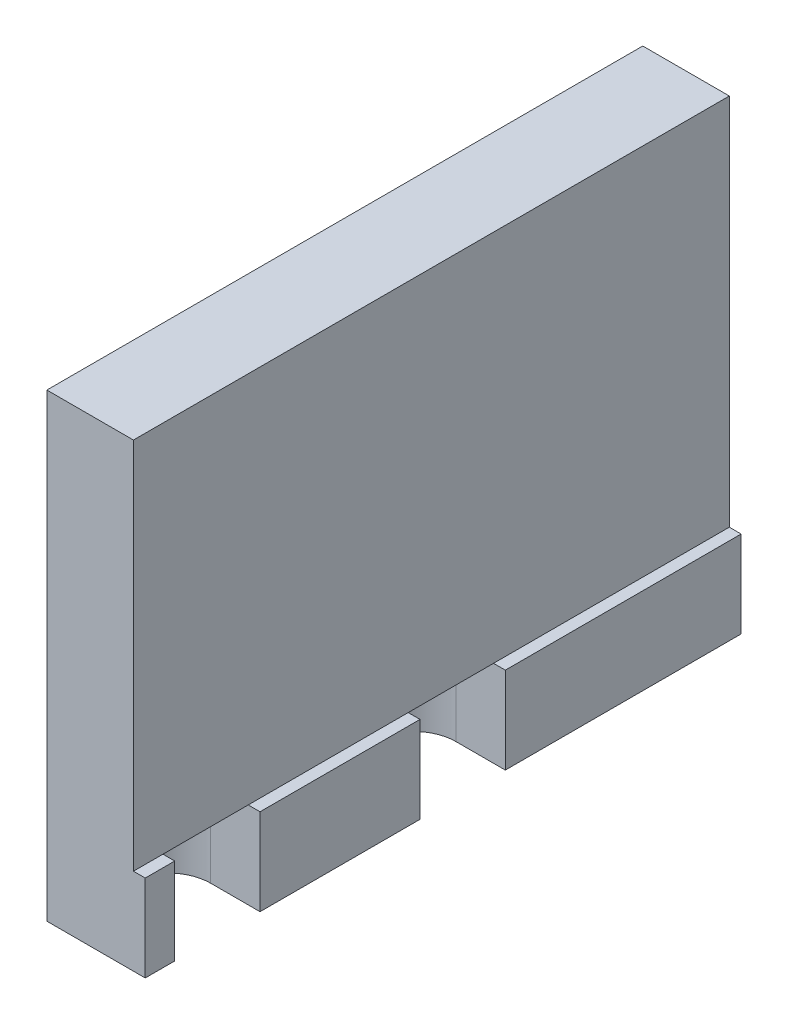
SolidWorks part; units mm, degrees
ref_plane "Front Plane" through (0, 0, 0) normal (0, 0, 1) x (1, 0, 0)
ref_plane "Top Plane" through (0, 0, 0) normal (0, 1, 0) x (1, 0, 0)
ref_plane "Right Plane" through (0, 0, 0) normal (1, 0, 0) x (0, 0, -1)
sketch "Sketch1" plane through (0, 0, 0) normal (0, 0, 1) x (1, 0, 0)
  line L0 (0, 0) -> (-6.8183, 0)
  line L1 (-6.8183, 0) -> (-6.8183, 76.4)
  line L2 (-6.8183, 76.4) -> (-0.8183, 76.4)
  line L3 (-0.8183, 76.4) -> (-0.8183, 6)
  line L4 (-0.8183, 6) -> (0, 6)
  line L5 (0, 6) -> (0, 0)
  line L6 (-0.8183, 44.108) -> (-0.8183, 16.1905) construction
  dimension "D1" = 6
  dimension "D2" = 6
extrude "Boss-Extrude1" add sketch "Sketch1" along normal blind 27 contours L5 L0 L1 L2 L3 L4
sketch "Sketch2" plane through (0, 0, 0) normal (0, 0, -1) x (-1, 0, 0)
  line L6 (0.8183, 6) -> (0, 6)
  line L7 (0, 6) -> (0, 0)
  line L8 (0, 0) -> (6.8183, 0)
  line L9 (6.8183, 0) -> (6.8183, 76.4)
  line L10 (6.8183, 76.4) -> (0.8183, 76.4)
  line L11 (0.8183, 76.4) -> (0.8183, 6)
  line L12 (0.8183, 6) -> (0, 6)
  line L13 (0, 6) -> (0, 0)
  line L14 (0, 0) -> (6.8183, 0)
  line L15 (6.8183, 0) -> (6.8183, 76.4)
  line L16 (6.8183, 76.4) -> (0.8183, 76.4)
  line L17 (0.8183, 76.4) -> (0.8183, 6)
  dimension "D2" = 6.8183
  dimension "D1" = 0
extrude "Boss-Extrude2" add sketch "Sketch2" along normal up to surface (14.3 mm away)
sketch "Sketch3" plane through (0, 6, 0) normal (0, 1, 0) x (1, 0, 0)
  line L0 (8.6817, -2.044) -> (2.6317, -2.044) construction
  line L1 (2.6317, -7.956) -> (8.6817, -7.956) construction
  line L2 (8.6817, -19.044) -> (2.6317, -19.044) construction
  line L3 (2.6317, -24.956) -> (8.6817, -24.956) construction
  line L12 (8.6817, -2.044) -> (-3.4183, -2.044)
  line L13 (-3.4183, -7.956) -> (8.6817, -7.956)
  line L14 (8.6817, -19.044) -> (-3.4183, -19.044)
  line L15 (-3.4183, -24.956) -> (8.6817, -24.956)
  arc A0 (8.6817, -24.956) -> (8.6817, -19.044) centre (8.6817, -22) ccw construction
  arc A1 (8.6817, -7.956) -> (8.6817, -2.044) centre (8.6817, -5) ccw construction
  arc A2 (8.6817, -24.956) -> (8.6817, -19.044) centre (8.6817, -22) ccw
  arc A3 (8.6817, -7.956) -> (8.6817, -2.044) centre (8.6817, -5) ccw
  arc A4 (-3.4183, -7.956) -> (-3.4183, -2.044) centre (-3.4183, -5) cw
  arc A5 (-3.4183, -24.956) -> (-3.4183, -19.044) centre (-3.4183, -22) cw
extrude "Cut-Extrude1" cut sketch "Sketch3" against normal up to surface (6 mm away) up to face at (-3.4091, 0, 6.35)
sketch "Sketch4" plane through (0, 0, -14.3) normal (0, 0, -1) x (-1, 0, 0)
  line L0 (6.8183, 76.4) -> (6.8183, 0) construction
  line L1 (0.8183, 76.4) -> (6.8183, 76.4)
  line L2 (0.8183, 76.4) -> (0.8183, 31.8812)
  line L3 (0.8183, 31.8812) -> (6.8183, 31.8812)
  line L4 (6.8183, 76.4) -> (6.8183, 31.8812)
extrude "Cut-Extrude2" cut sketch "Sketch4" against normal blind 66
